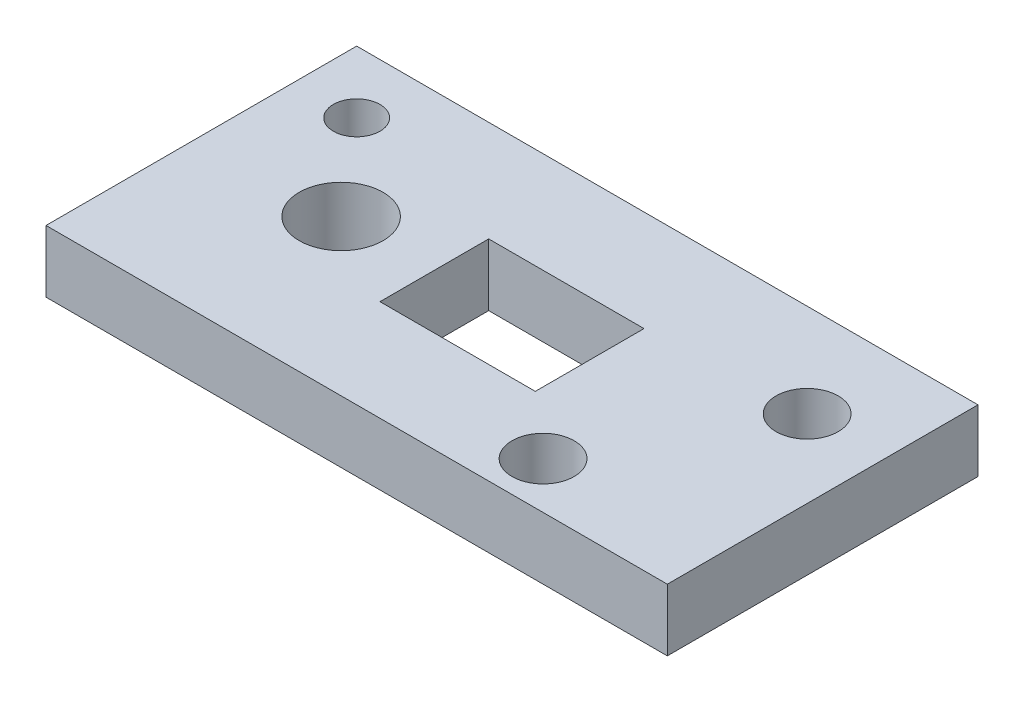
SolidWorks part; units mm, degrees
ref_plane "Front Plane" through (0, 0, 0) normal (0, 0, 1) x (1, 0, 0)
ref_plane "Top Plane" through (0, 0, 0) normal (0, 1, 0) x (1, 0, 0)
ref_plane "Right Plane" through (0, 0, 0) normal (1, 0, 0) x (0, 0, -1)
sketch "Sketch1" plane through (0, 0, 0) normal (0, 1, 0) x (1, 0, 0)
  line L1 (-100, 50) -> (100, 50)
  line L2 (-100, 50) -> (-100, -50)
  line L3 (-100, -50) -> (100, -50)
  line L4 (100, 50) -> (100, -50)
  line L5 (-100, 50) -> (100, -50) construction
  line L6 (-100, -50) -> (100, 50) construction
  point P0 (0, 0)
extrude "Boss-Extrude1" add sketch "Sketch1" along normal mid plane 20
sketch "Sketch2" plane through (0, 10, 0) normal (0, 1, 0) x (1, 0, 0)
  line L0 (-100, -50) -> (100, -50) construction
  line L1 (-25, 17.5) -> (25, 17.5)
  line L2 (-25, 17.5) -> (-25, -17.5)
  line L3 (-25, -17.5) -> (25, -17.5)
  line L4 (25, 17.5) -> (25, -17.5)
  line L5 (-25, 17.5) -> (25, -17.5) construction
  line L6 (-25, -17.5) -> (25, 17.5) construction
  line L7 (100, 50) -> (-100, 50) construction
  line L8 (-100, 50) -> (-100, -50) construction
  line L9 (100, -50) -> (100, 50) construction
  circle A0 centre (-80, 30) radius 7.5
  circle A1 centre (-55, 0) radius 13.5
  circle A2 centre (75, 20) radius 10
  circle A3 centre (45, -35) radius 10
  point P0 (0, 0)
  dimension "D3" = 27
  dimension "D4" = 15
  dimension "D5" = 20
  dimension "D6" = 20
  dimension "D8" = 30
  dimension "D9" = 30
  dimension "D10" = 15
  dimension "D13" = 55
  dimension "D14" = 25
  dimension "D1" = 50
  dimension "D2" = 35
  dimension "D7" = 50
  dimension "D11" = 20
  dimension "D12" = 45
extrude "Cut-Extrude1" cut sketch "Sketch2" against normal through all
